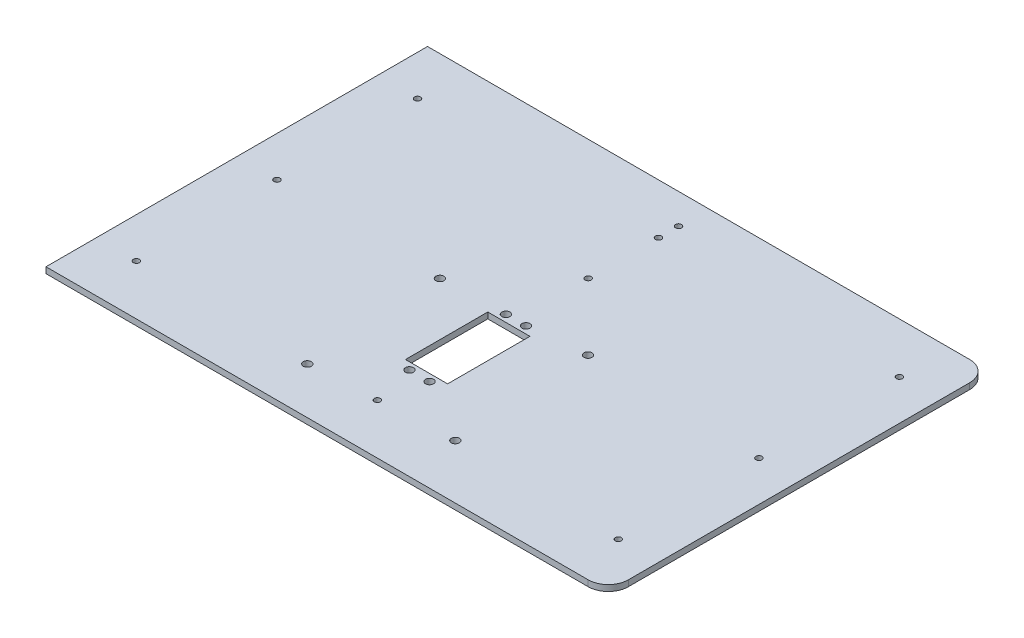
SolidWorks part; units mm, degrees
ref_plane "前视基准面" through (0, 0, 0) normal (0, 0, 1) x (1, 0, 0)
ref_plane "上视基准面" through (0, 0, 0) normal (0, 1, 0) x (1, 0, 0)
ref_plane "右视基准面" through (0, 0, 0) normal (1, 0, 0) x (0, 0, -1)
sketch "草图1" plane through (0, 0, 0) normal (0, 1, 0) x (1, 0, 0)
  line L1 (140, 95) -> (-140, 95)
  line L2 (140, 95) -> (140, -95)
  line L3 (140, -95) -> (-140, -95)
  line L4 (-140, 95) -> (-140, -95)
  line L5 (10.5, -45.5) -> (-10.5, -45.5)
  line L6 (10.5, -45.5) -> (10.5, -4.5)
  line L7 (10.5, -4.5) -> (-10.5, -4.5)
  line L8 (-10.5, -45.5) -> (-10.5, -4.5)
  circle A0 centre (5, -1) radius 2
  circle A1 centre (-5, -1) radius 2
  circle A2 centre (-5, -49) radius 2
  circle A3 centre (-33.0281, -71.8699) radius 2
  circle A4 centre (5, -49) radius 2
  circle A5 centre (-36.8699, -1.9719) radius 2
  circle A7 centre (33.0281, 1.8699) radius 2
  circle A9 centre (36.8699, -68.0281) radius 2
  point P14 (36.8699, -68.0281)
  point P15 (-36.8699, -1.9719)
  point P18 (-33.0281, -71.8699)
  point P19 (33.0281, 1.8699)
  point P22 (0, 0)
  point P26 (0, -35)
  point P34 (0, 0)
extrude "凸台-拉伸1" add sketch "草图1" along normal blind 3
fillet "圆角1" radius 10 2 edges at (140, 1.5, 95) (140, 1.5, -95)
sketch "草图2" plane through (0, 3, 0) normal (0, 1, 0) x (1, 0, 0)
  circle A0 centre (120, -70) radius 1.5
  circle A1 centre (0, -70) radius 1.5
  circle A2 centre (-120, -70) radius 1.5
extrude "切除-拉伸1" cut sketch "草图2" against normal blind 10
mirror "镜向1" about plane through (0, 0, 0) normal (0, 0, 1) of "切除-拉伸1"
sketch "草图3" plane through (0, 3, 0) normal (0, 1, 0) x (1, 0, 0)
  circle A0 centre (120, 0) radius 1.5
  circle A1 centre (-120, 0) radius 1.5
extrude "切除-拉伸2" cut sketch "草图3" against normal blind 10
sketch "草图4" plane through (0, 3, 0) normal (0, 1, 0) x (1, 0, 0)
  circle A0 centre (0, 80) radius 1.5
  circle A1 centre (0, 35) radius 1.5
extrude "切除-拉伸3" cut sketch "草图4" against normal blind 10
